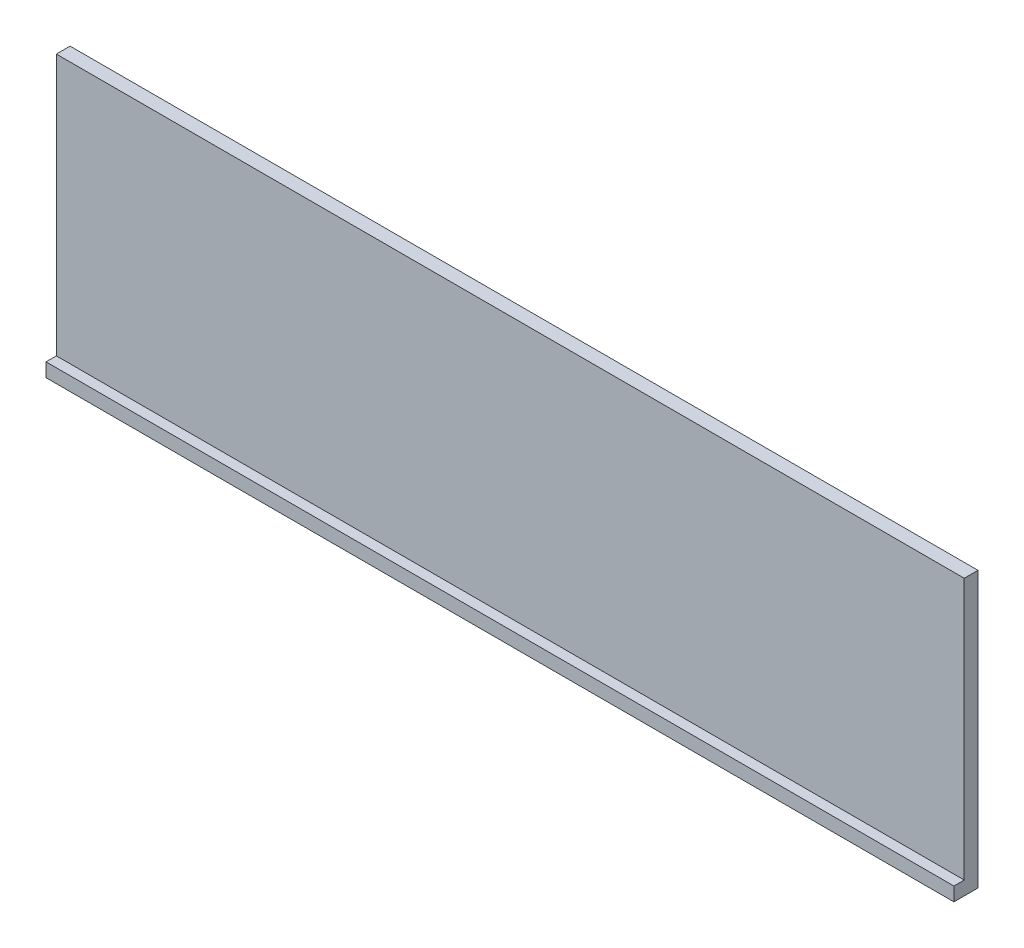
SolidWorks part; units mm, degrees
ref_plane "前视基准面" through (0, 0, 0) normal (0, 0, 1) x (1, 0, 0)
ref_plane "上视基准面" through (0, 0, 0) normal (0, 1, 0) x (1, 0, 0)
ref_plane "右视基准面" through (0, 0, 0) normal (1, 0, 0) x (0, 0, -1)
other "Configuration Table"
sketch "草图1" plane through (0, 0, 0) normal (0, 0, 1) x (1, 0, 0)
  line L1 (-29.9267, 22.0599) -> (102.0733, 22.0599)
  line L2 (-29.9267, 22.0599) -> (-29.9267, -17.9401)
  line L3 (-29.9267, -17.9401) -> (102.0733, -17.9401)
  line L4 (102.0733, 22.0599) -> (102.0733, -17.9401)
  dimension "D1" = 40
  dimension "D2" = 132
extrude "凸台-拉伸1" add sketch "草图1" along normal blind 2
sketch "草图2" plane through (0, 0, 2) normal (0, 0, 1) x (1, 0, 0)
  line L0 (-29.9267, -15.9401) -> (102.0733, -15.9401)
  line L1 (-29.9267, 22.0599) -> (-29.9267, -17.9401) construction
  line L2 (102.0733, -17.9401) -> (102.0733, 22.0599) construction
  line L3 (-29.9267, -17.9401) -> (102.0733, -17.9401) construction
  line L4 (-29.9267, -15.9401) -> (-29.9267, -17.9401)
  line L5 (-29.9267, -17.9401) -> (102.0733, -17.9401)
  line L6 (102.0733, -17.9401) -> (102.0733, -15.9401)
  dimension "D1" = 2
extrude "凸台-拉伸2" add sketch "草图2" along normal blind 1.5
